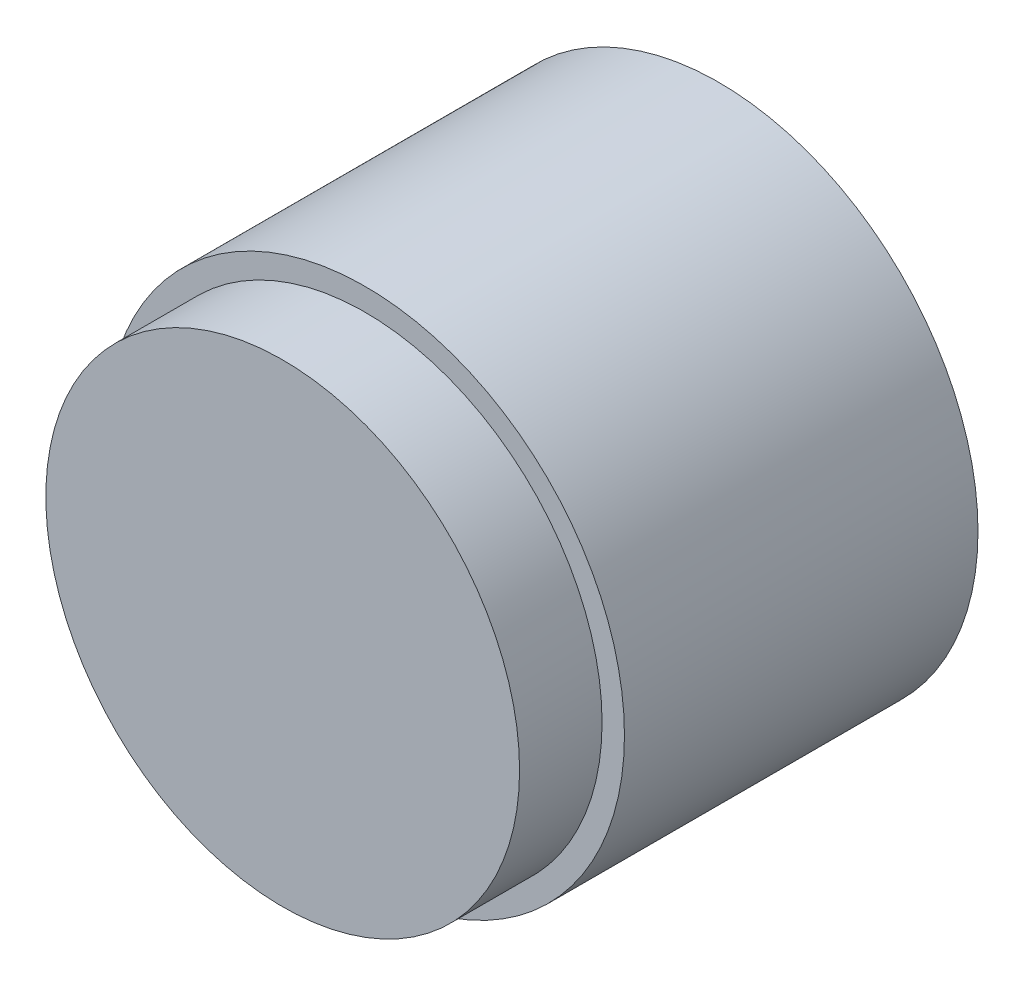
SolidWorks part; units mm, degrees
ref_plane "Front Plane" through (0, 0, 0) normal (1, 0, 0) x (0, 1, 0)
ref_plane "Top Plane" through (0, 0, 0) normal (0, 0, 1) x (0, 1, 0)
ref_plane "Right Plane" through (0, 0, 0) normal (0, 1, 0) x (-1, 0, 0)
sketch "Sketch1" plane through (0, 0, 0) normal (0, 0, 1) x (0, 1, 0)
  circle A0 centre (0, 0) radius 11
  dimension "D1" = 22
extrude "Boss-Extrude1" add sketch "Sketch1" along normal blind 15 contours A0
sketch "Sketch2" plane through (0, 0, 15) normal (0, 0, 1) x (1, 0, 0)
  circle A0 centre (0, 0) radius 10.05
  dimension "D1" = 20.1
extrude "Boss-Extrude2" add sketch "Sketch2" along normal blind 3.5
